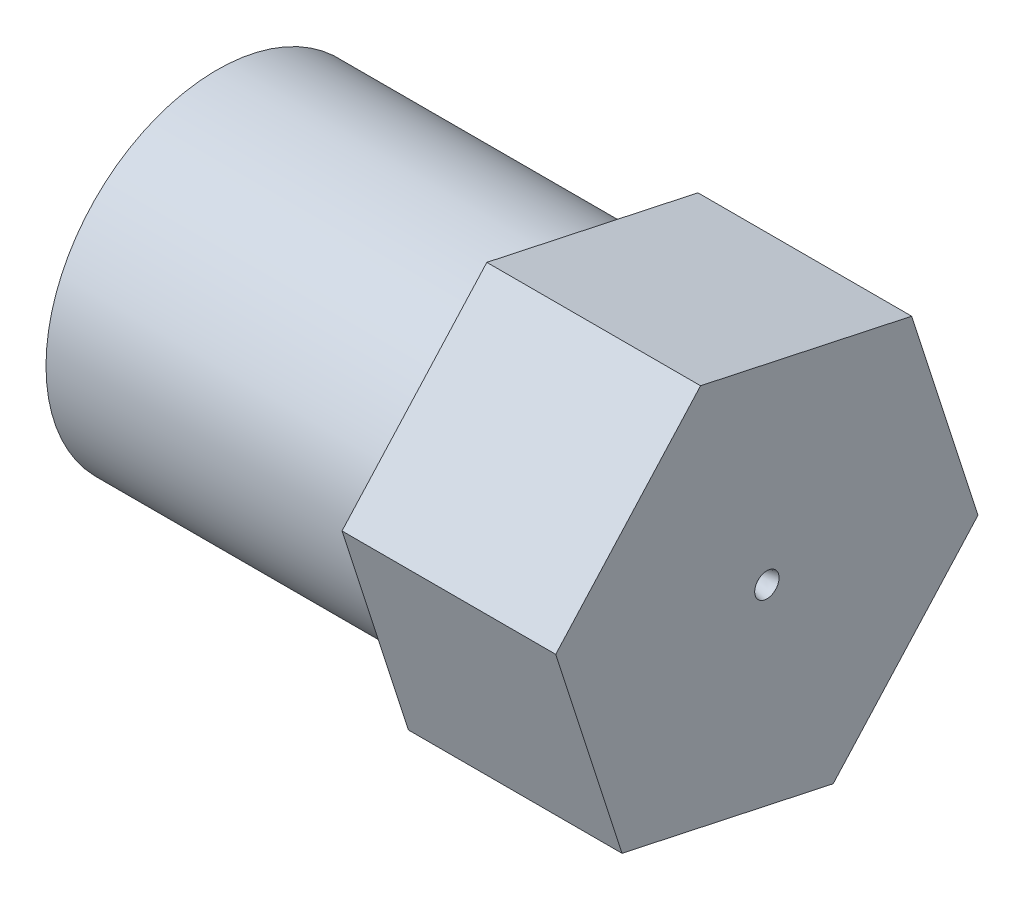
SolidWorks part; units mm, degrees
ref_plane "Front Plane" through (0, 0, 0) normal (0, 0, 1) x (1, 0, 0)
ref_plane "Top Plane" through (0, 0, 0) normal (0, 1, 0) x (1, 0, 0)
ref_plane "Right Plane" through (0, 0, 0) normal (1, 0, 0) x (0, 0, -1)
sketch "Sketch1" plane through (0, 0, 0) normal (0, 0, 1) x (1, 0, 0)
  line L0 (0, 0) -> (0.925, 0) construction
  line L1 (0.0684, 0.5121) -> (0.925, 0.8238) construction
  line L2 (-0.5303, 0.7197) -> (-3.3257, 3.5151)
  line L3 (-31.75, 4.445) -> (-31.75, 10.16) construction
  line L4 (-5.5708, 4.445) -> (-31.75, 4.445) construction
  line L5 (-31.75, 10.16) -> (-11.775, 10.16)
  line L6 (0.925, 10.16) -> (0.925, 0.7246)
  line L7 (0.925, 0.7246) -> (13.2352, 2.4547) construction
  line L8 (-11.775, 10.16) -> (0.925, 10.16)
  line L9 (-5.5708, 4.445) -> (-13.462, 4.445)
  line L10 (-19.939, 5.461) -> (-19.939, 6.8199)
  line L11 (-20.066, 6.9469) -> (-24.892, 6.9469)
  line L12 (-24.892, 6.9469) -> (-24.892, 7.8994)
  line L13 (-25.019, 8.0264) -> (-31.115, 8.0264)
  line L14 (-31.75, 10.16) -> (-31.75, 8.6614)
  line L15 (0, 0) -> (-31.75, 0) construction
  line L16 (-13.462, 4.445) -> (-13.462, 4.699)
  line L17 (-13.589, 4.826) -> (-19.304, 4.826)
  arc A0 (-0.5303, 0.7197) -> (0, 0.5) centre (0, 1.25) ccw
  arc A1 (0, 0.5) -> (0.0684, 0.5121) centre (0, 0.7) ccw
  arc A2 (-3.3257, 3.5151) -> (-5.5708, 4.445) centre (-5.5708, 1.27) ccw
  arc A3 (-31.115, 8.0264) -> (-31.75, 8.6614) centre (-31.115, 8.6614) cw
  arc A4 (-19.304, 4.826) -> (-19.939, 5.461) centre (-19.304, 5.461) cw
  arc A5 (-13.462, 4.699) -> (-13.589, 4.826) centre (-13.589, 4.699) ccw
  arc A6 (-19.939, 6.8199) -> (-20.066, 6.9469) centre (-20.066, 6.8199) ccw
  arc A7 (-24.892, 7.8994) -> (-25.019, 8.0264) centre (-25.019, 7.8994) ccw
  parabola Q0 (0.925, 0.7246) -> (0.0684, 0.5121) focus (0.7745, -1.4278) apex (0.0684, 0.5121)
  point P30 (-31.75, 8.0264)
  point P39 (-24.892, 8.0264)
  dimension "D3" = 0.75
  dimension "D4" = 0.2
  dimension "D11" = 3.175
  dimension "D12" = 8
  dimension "D14" = 6.9469
  dimension "D20" = 0.635
  dimension "D21" = 0.127
  dimension "D2" = 0.925
  dimension "D5" = 0.7246
  dimension "D6" = 20
  dimension "D7" = 45
  dimension "D8" = 8.0264
  dimension "D9" = 31.75
  dimension "D10" = 10.16
  dimension "D13" = 12.7
  dimension "D15" = 4.445
  dimension "D16" = 6.858
  dimension "D17" = 11.811
  dimension "D18" = 18.288
  dimension "D19" = 4.826
  dimension "D22" = 0.5
revolve "Revolve1" add sketch "Sketch1" angle 360 about L0
sketch "Sketch4" plane through (0.925, 0, 0) normal (1, 0, 0) x (0, 0, -1)
  line L1 (3.9404, -12.2116) -> (12.5458, -2.6933)
  line L2 (12.5458, -2.6933) -> (8.6054, 9.5183)
  line L3 (8.6054, 9.5183) -> (-3.9404, 12.2116)
  line L4 (-3.9404, 12.2116) -> (-12.5458, 2.6933)
  line L5 (-12.5458, 2.6933) -> (-8.6054, -9.5183)
  line L6 (-8.6054, -9.5183) -> (3.9404, -12.2116)
  circle A0 centre (0, 0) radius 10.16
  circle A1 centre (0, 0) radius 10.16 construction
  circle A2 centre (0, 0) radius 11.1125 construction
  circle M1 centre (0, 0) radius 10.16
  dimension "D1" = 22.225
extrude "Boss-Extrude1" add sketch "Sketch4" against normal blind 12.7 contours L4 L5 M1 | L3 L4 M1 | L2 L3 M1 | L1 L2 M1 | L6 L1 M1 | L5 L6 M1
fillet "Fillet1" radius 0.635 1 edges at (-11.775, 0, -10.16)
equation "\"D3@Sketch1\" = 1.5 * \"D22@Sketch1\""
equation "\"D4@Sketch1\"  = .4 * \"D22@Sketch1\""
equation "\"D5@Sketch1\"=\"D22@Sketch1\" * ( \"er\") ^ .5"
equation "\"er\"= 2.1"
